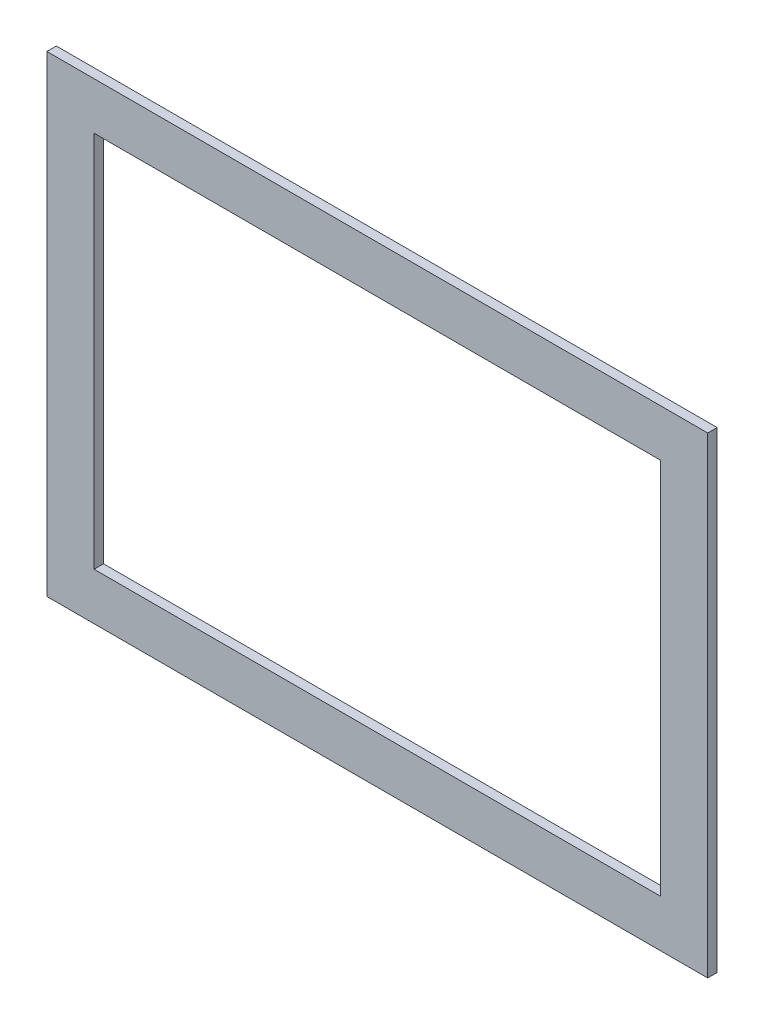
SolidWorks part; units mm, degrees
material "Balsa"
ref_plane "Plan de face" through (0, 0, 0) normal (0, 0, 1) x (1, 0, 0)
ref_plane "Plan de dessus" through (0, 0, 0) normal (0, 1, 0) x (1, 0, 0)
ref_plane "Plan de droite" through (0, 0, 0) normal (1, 0, 0) x (0, 0, -1)
sketch "Esquisse1" plane through (0, 0, 0) normal (0, 0, 1) x (1, 0, 0)
  line L1 (0, 0) -> (-700, 0)
  line L2 (0, 0) -> (0, 500)
  line L3 (0, 500) -> (-700, 500)
  line L4 (-700, 0) -> (-700, 500)
  dimension "D1" = 700
  dimension "D2" = 500
extrude "Boss.-Extru.1" add sketch "Esquisse1" along normal blind 10
sketch "Esquisse2" plane through (0, 0, 10) normal (0, 0, 1) x (1, 0, 0)
  line L0 (0, 500) -> (-700, 500) construction
  line L1 (-650, 450) -> (-50, 450)
  line L2 (-650, 450) -> (-650, 50)
  line L3 (-650, 50) -> (-50, 50)
  line L4 (-50, 450) -> (-50, 50)
  line L5 (-700, 500) -> (-700, 0) construction
  line L6 (-700, 0) -> (0, 0) construction
  line L7 (0, 0) -> (0, 500) construction
  dimension "D1" = 50
  dimension "D2" = 50
  dimension "D3" = 50
  dimension "D4" = 50
extrude "Enlèv. mat.-Extru.1" cut sketch "Esquisse2" against normal blind 10
